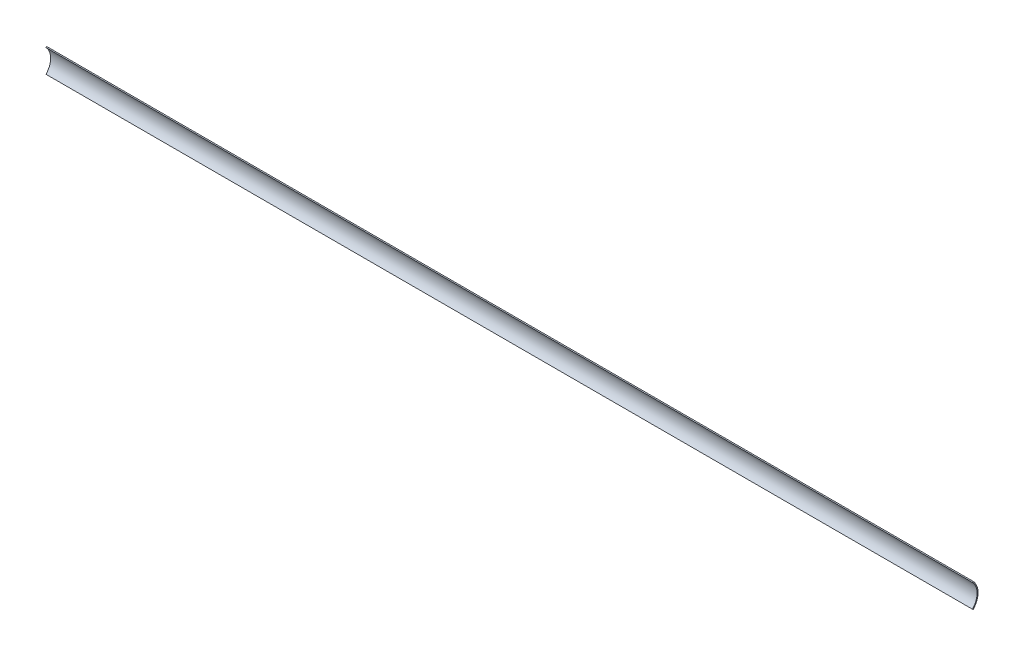
SolidWorks part; units mm, degrees
material "AISI 316 Stainless Steel Sheet (SS)"
ref_plane "Front Plane" through (0, 0, 0) normal (1, 0, 0) x (0, 1, 0)
ref_plane "Top Plane" through (0, 0, 0) normal (0, 0, 1) x (0, 1, 0)
ref_plane "Right Plane" through (0, 0, 0) normal (0, 1, 0) x (-1, 0, 0)
sketch "Sketch1" plane through (0, 0, 0) normal (1, 0, 0) x (0, 1, 0)
  arc A0 (0, 1) -> (5, 1) centre (2.5, 3.625) ccw
  point P3 (2.5, 0)
  point P5 (0, 0)
  point P6 (0, 0)
  point P7 (5, 1.2607)
  dimension "D1" = 5
  dimension "D2" = 1
extrude "Extrude-Thin1" add sketch "Sketch1" along normal blind 200 thin
